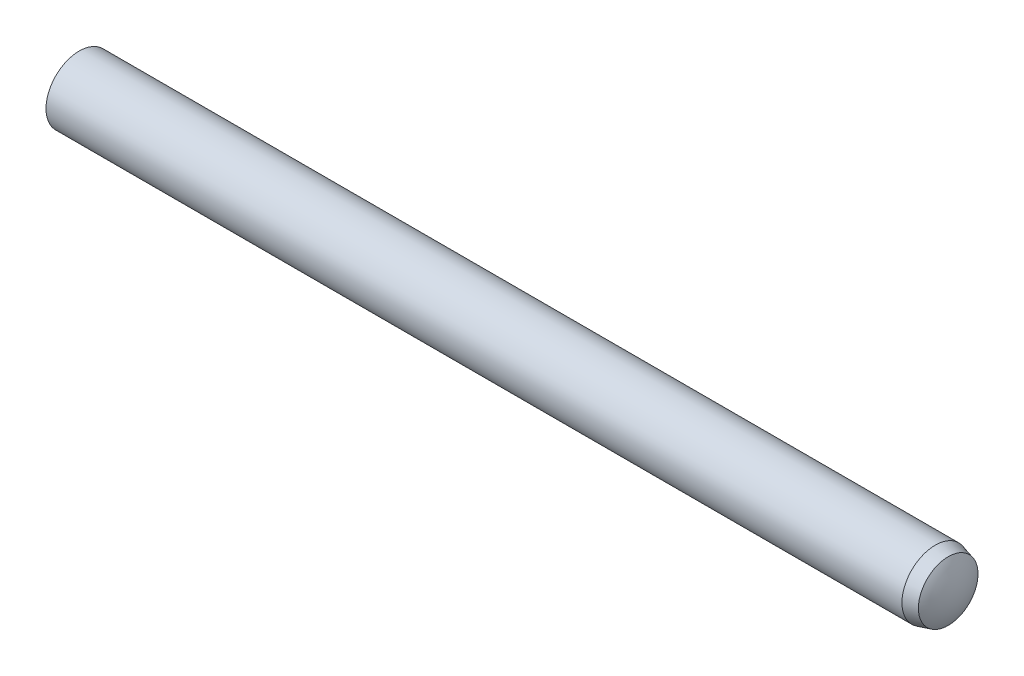
SolidWorks part; units mm, degrees
ref_plane "Front Plane" through (0, 0, 0) normal (0, 0, 1) x (1, 0, 0)
ref_plane "Top Plane" through (0, 0, 0) normal (0, 1, 0) x (1, 0, 0)
ref_plane "Right Plane" through (0, 0, 0) normal (1, 0, 0) x (0, 0, -1)
sketch "Sketch1" plane through (0, 0, 0) normal (0, 0, 1) x (1, 0, 0)
  line L0 (-20, 0) -> (20, 0) construction
  line L1 (20, 1.5) -> (20, -1.5) construction
  line L2 (-20, 1.5) -> (-20, -1.5) construction
  line L3 (19.025, 1.5) -> (19.025, -1.5) construction
  line L4 (-19.55, 1.5) -> (-19.55, -1.5) construction
  line L5 (-20, 0) -> (-19.55, 0) construction
  line L6 (20, 0) -> (19.025, 0) construction
  line L7 (19.61, 1.5) -> (19.61, -1.5) construction
  dimension "Dia" = 3
  dimension "Length" = 40
  dimension "D1" = 0.975
  dimension "D2" = 0.45
  dimension "D3" = 0.585
sketch "Sketch2" plane through (0, 0, 0) normal (1, 0, 0) x (0, 0, -1)
  circle A0 centre (0, 0) radius 1.5
extrude "Extrude1" add sketch "Sketch2" against normal up to vertex (20 mm away) and the other way up to vertex (20 mm away) up to point (-20, 0, 0) other way up to point (20, 0, 0)
sketch "Sketch5" plane through (0, 0, 0) normal (0, 0, 1) x (1, 0, 0)
  line L0 (19.025, 1.5) -> (19.025, 2)
  line L1 (19.025, 2) -> (20.5, 2)
  line L2 (20.5, 2) -> (20.5, 0)
  line L3 (20, 0) -> (20.5, 0)
  line L5 (-19.55, 1.5) -> (-19.55, 2)
  line L6 (-19.55, 2) -> (-20.5, 2)
  line L7 (-20.5, 2) -> (-20.5, 0)
  line L8 (19.025, 1.5) -> (19.61, 1.3432)
  line L10 (-20, 0) -> (-20.5, 0)
  line L11 (-20, 1.5) -> (-20, -1.5) construction
  line L13 (19.025, 1.5) -> (19.025, -1.5) construction
  line L15 (-20, 0) -> (20, 0) construction
  line L16 (19.61, 1.5) -> (19.61, -1.5) construction
  line L17 (20, 1.5) -> (20, -1.5) construction
  arc A0 (19.61, 1.3432) -> (20, 0) centre (17.4918, 0) cw
  arc A1 (-19.55, 1.5) -> (-20, 0) centre (-17.275, 0) ccw
  dimension "D1" = 15
  dimension "D2" = 0.5
revolve "Cut-Revolve1" cut sketch "Sketch5" angle 360 about L0
equation "\"D1@Sketch1\" = \"Dia@Sketch1\"*.325"
equation "\"D2@Sketch1\" = \"Dia@Sketch1\"*.15"
equation "\"D3@Sketch1\" = \"D1@Sketch1\"*.6"
